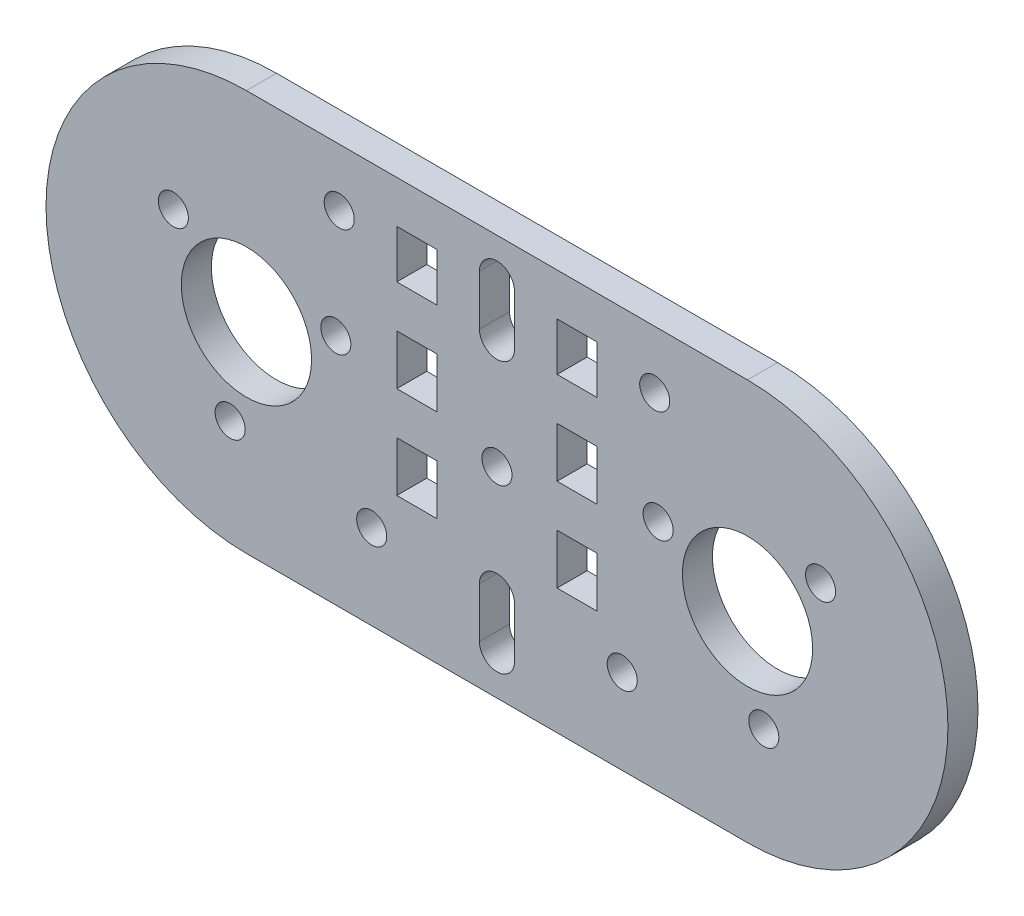
SolidWorks part; units mm, degrees
ref_plane "前视基准面" through (0, 0, 0) normal (0, 0, 1) x (1, 0, 0)
ref_plane "上视基准面" through (0, 0, 0) normal (0, 1, 0) x (1, 0, 0)
ref_plane "右视基准面" through (0, 0, 0) normal (1, 0, 0) x (0, 0, -1)
sketch "草图1" plane through (0, 0, 0) normal (0, 0, 1) x (1, 0, 0)
  line L0 (-11.3774, 24.1048) -> (38.6226, 24.1048) construction
  line L1 (13.6226, 24.1048) -> (13.6226, 7.3546) construction
  line L2 (38.6226, 44.1048) -> (19.6226, 44.1048)
  line L3 (-11.3774, 4.1048) -> (38.6226, 4.1048)
  line L4 (26.1226, 24.1048) -> (26.1226, 12.583) construction
  line L5 (23.6226, 35.0748) -> (19.6226, 35.0748)
  line L6 (23.6226, 25.8448) -> (19.6226, 25.8448)
  line L7 (7.6226, 39.8748) -> (7.6226, 35.0748)
  line L8 (3.6226, 39.8748) -> (7.6226, 39.8748)
  line L9 (3.6226, 35.0748) -> (3.6226, 39.8748)
  line L10 (3.6226, 30.8448) -> (7.6226, 30.8448)
  line L11 (3.6226, 25.8448) -> (3.6226, 30.8448)
  line L12 (7.6226, 30.8448) -> (7.6226, 25.8448)
  line L13 (7.6226, 21.6148) -> (7.6226, 16.6148)
  line L14 (3.6226, 16.6148) -> (3.6226, 21.6148)
  line L15 (7.6226, 16.6148) -> (3.6226, 16.6148)
  line L16 (3.6226, 21.6148) -> (7.6226, 21.6148)
  line L17 (3.6226, 25.8448) -> (7.6226, 25.8448)
  line L18 (3.6226, 35.0748) -> (7.6226, 35.0748)
  line L19 (17.6226, 44.1048) -> (9.6226, 44.1048)
  line L22 (23.6226, 21.6148) -> (19.6226, 21.6148)
  line L23 (-11.3774, 44.1048) -> (7.6226, 44.1048)
  line L26 (19.6226, 44.1048) -> (17.6226, 44.1048)
  line L30 (7.6226, 44.1048) -> (9.6226, 44.1048)
  line L34 (24.6226, 12.583) -> (24.6226, 38.3621) construction
  line L35 (23.6226, 24.1048) -> (23.6226, 47.2442) construction
  line L36 (19.6226, 24.1048) -> (19.6226, 38.3621) construction
  line L37 (19.6226, 16.6148) -> (23.6226, 16.6148)
  line L38 (23.6226, 16.6148) -> (23.6226, 21.6148)
  line L39 (13.6226, 20.8549) -> (13.6226, 4.1048) construction
  line L40 (19.6226, 21.6148) -> (19.6226, 16.6148)
  line L41 (19.6226, 30.8448) -> (19.6226, 25.8448)
  line L42 (11.8726, 8.1271) -> (11.8726, 13.1271)
  line L43 (23.6226, 25.8448) -> (23.6226, 30.8448)
  line L44 (23.6226, 30.8448) -> (19.6226, 30.8448)
  line L45 (15.3726, 8.1271) -> (15.3726, 13.1271)
  line L46 (23.6226, 35.0748) -> (23.6226, 39.8748)
  line L47 (23.6226, 39.8748) -> (19.6226, 39.8748)
  line L48 (19.6226, 39.8748) -> (19.6226, 35.0748)
  line L49 (15.3726, 40.1271) -> (15.3726, 35.1271)
  line L50 (11.8726, 40.1271) -> (11.8726, 35.1271)
  circle A0 centre (-11.3774, 24.1048) radius 9.5 construction
  circle A1 centre (29.7039, 27.3769) radius 1.5
  circle A2 centre (-2.4587, 27.3769) radius 1.5
  circle A3 centre (-13.003, 14.7449) radius 1.5
  circle A4 centre (38.6226, 24.1048) radius 9.5 construction
  circle A5 centre (-18.6705, 30.1925) radius 1.5
  circle A6 centre (45.9157, 30.1925) radius 1.5
  circle A8 centre (-11.3774, 24.1048) radius 6.5
  circle A9 centre (38.6226, 24.1048) radius 6.5
  circle A10 centre (38.6226, 24.1048) radius 17 construction
  circle A11 centre (29.3636, 38.3621) radius 1.5
  circle A12 centre (13.6226, 24.1048) radius 1.5
  circle A13 centre (-11.3774, 24.1048) radius 12.5 construction
  circle A14 centre (38.6226, 24.1048) radius 12.5 construction
  circle A15 centre (-11.3774, 24.1048) radius 17 construction
  circle A16 centre (-2.1184, 38.3621) radius 1.5
  circle A17 centre (40.2482, 14.7449) radius 1.5
  arc A18 (-11.3774, 44.1048) -> (-11.3774, 4.1048) centre (-11.3774, 24.1048) ccw
  arc A19 (38.6226, 4.1048) -> (38.6226, 44.1048) centre (38.6226, 24.1048) ccw
  circle A20 centre (26.1226, 12.583) radius 1.5
  circle A21 centre (1.1226, 12.583) radius 1.5
  arc A25 (15.3726, 13.1271) -> (11.8726, 13.1271) centre (13.6226, 13.1271) ccw
  arc A27 (11.8726, 8.1271) -> (15.3726, 8.1271) centre (13.6226, 8.1271) ccw
  arc A28 (11.8726, 40.1271) -> (15.3726, 40.1271) centre (13.6226, 40.1271) cw
  arc A29 (15.3726, 35.1271) -> (11.8726, 35.1271) centre (13.6226, 35.1271) cw
  point P15 (-11.3774, 24.1048)
  point P25 (38.6226, 24.1048)
  point P26 (38.6226, 24.1048)
  point P35 (-11.3774, 24.1048)
  point P38 (9.6226, 44.1048)
  point P40 (13.6226, 24.1048)
  point P42 (38.6226, 24.1048)
  point P43 (-11.3774, 24.1048)
  point P48 (13.6226, 12.0848)
  point P60 (13.6226, 24.1048)
  point P61 (13.6226, 12.0848)
  point P64 (13.6226, 27.3769)
  point P71 (17.6226, 44.1048)
  point P81 (13.6226, 47.3769)
  point P107 (9.6226, 40.8549)
  point P108 (13.6226, 20.8549)
  point P109 (13.6226, 8.8349)
  point P111 (13.6226, 20.8549)
  point P112 (13.6226, 8.8349)
  point P113 (13.6226, 24.1271)
  point P122 (17.6226, 40.8549)
  point P130 (13.6226, 44.1271)
  dimension "D2" = 3
  dimension "D4" = 19
  dimension "D5" = 25
  dimension "D1" = 50
  dimension "D6" = 20
  dimension "D7" = 11.5217
  dimension "D8" = 4
  dimension "D9" = 12.02
  dimension "D17" = 1
  dimension "D18" = 4
  dimension "D3" = 3
extrude "凸台-拉伸1" add sketch "草图1" along normal blind 3
